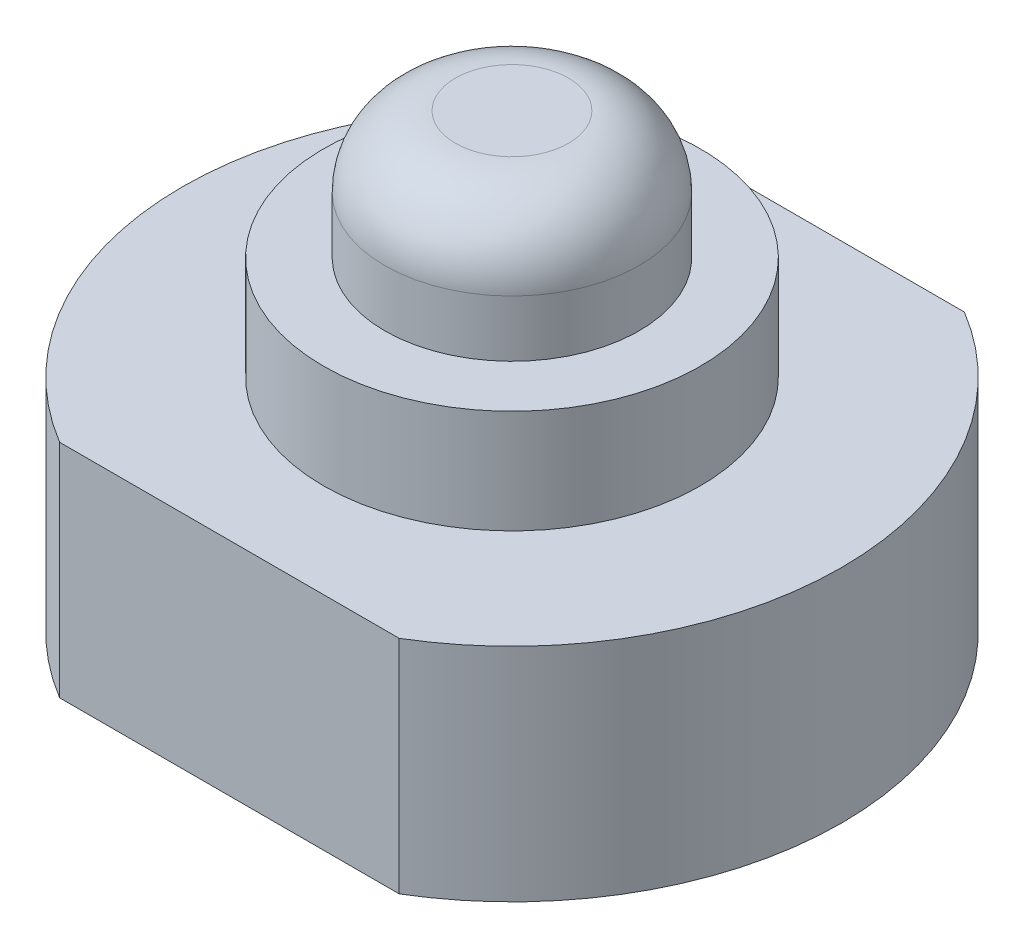
SolidWorks part; units mm, degrees
ref_plane "Front Plane" through (0, 0, 0) normal (0, 0, 1) x (1, 0, 0)
ref_plane "Top Plane" through (0, 0, 0) normal (0, 1, 0) x (1, 0, 0)
ref_plane "Right Plane" through (0, 0, 0) normal (1, 0, 0) x (0, 0, -1)
sketch "Sketch1" plane through (0, 0, 0) normal (0, 1, 0) x (1, 0, 0)
  line L0 (-3.6044, 6) -> (3.6056, 6)
  line L1 (-3.6044, -6) -> (3.6056, -6)
  arc A1 (3.6056, 6) -> (3.6056, -6) centre (0.0012, 0) cw
  arc A2 (-3.6044, 6) -> (-3.6044, -6) centre (0, 0) ccw
  point P6 (-6.9994, 0)
  point P7 (7.0006, 0)
  point P8 (0, 0)
  point P10 (0, 0)
  point P11 (0, 0)
  point P12 (0, 0)
  point P13 (0, 0)
  dimension "D5" = 6.9994
  dimension "D6" = 6.9994
  dimension "D1" = 7.21
  dimension "D2" = 12
  dimension "D3" = 14
  dimension "D4" = 7.21
extrude "Boss-Extrude1" add sketch "Sketch1" along normal blind 4.7
sketch "Sketch2" plane through (0, 4.7, 0) normal (0, 1, 0) x (1, 0, 0)
  circle A0 centre (0, 0) radius 4
  dimension "D1" = 8
extrude "Boss-Extrude2" add sketch "Sketch2" along normal blind 2.2
sketch "Sketch3" plane through (0, 6.9, 0) normal (0, 1, 0) x (1, 0, 0)
  circle A0 centre (0, 0) radius 2.7
  dimension "D1" = 5.4
extrude "Boss-Extrude3" add sketch "Sketch3" along normal blind 2.7
fillet "Fillet1" radius 1.5 1 edges at (0, 9.6, 2.7)
